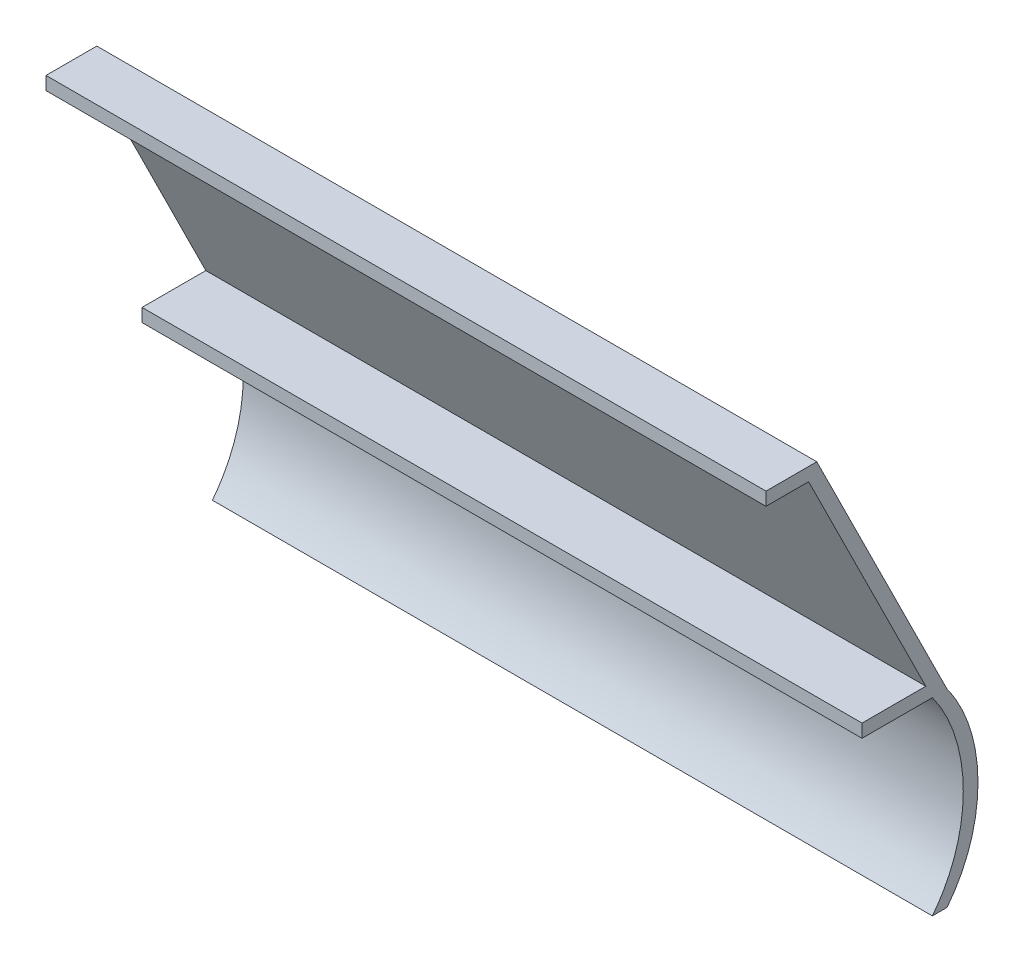
SolidWorks part; units mm, degrees
ref_plane "前视基准面" through (0, 0, 0) normal (0, 0, 1) x (1, 0, 0)
ref_plane "上视基准面" through (0, 0, 0) normal (0, 1, 0) x (1, 0, 0)
ref_plane "右视基准面" through (0, 0, 0) normal (1, 0, 0) x (0, 0, -1)
sketch "草图1" plane through (0, 0, 0) normal (1, 0, 0) x (0, 0, -1)
  line L0 (0, 0) -> (9.7, 0) construction
  line L1 (9.7, 0) -> (9.7, -56.63) construction
  line L2 (9.7, -56.63) -> (37.85, -56.63) construction
  line L3 (9.7, 0) -> (36.3587, -53.63)
  line L4 (37.85, -56.63) -> (37.85, -99.63) construction
  line L5 (0, 0) -> (0, 3)
  line L6 (12.8929, 0.3164) -> (41.0429, -56.3136)
  line L7 (0, 3) -> (11.5589, 3)
  line L8 (12.8929, 0.3164) -> (11.5589, 3)
  line L9 (41.0429, -56.3136) -> (41.2002, -56.63)
  line L10 (41.2002, -99.63) -> (37.85, -99.63)
  line L11 (0, 0) -> (9.7, 0)
  line L12 (37.85, -56.63) -> (21.85, -56.63)
  line L13 (21.85, -56.63) -> (21.85, -53.63)
  line L14 (21.85, -53.63) -> (36.3587, -53.63)
  spline S0 degree 3 poles (37.85, -56.63) (46.954, -69.0607) (47.4998, -87.4222) (37.85, -99.63) knots 0 0 0 0 1 1 1 1
  spline S1 degree 3 poles (41.2002, -56.63) (50.3042, -69.0607) (50.85, -87.4222) (41.2002, -99.63) knots 0 0 0 0 1 1 1 1
  dimension "D1" = 9.7
  dimension "D2" = 56.63
  dimension "D3" = 28.15
  dimension "D4" = 43
  dimension "D5" = 3
  dimension "D6" = 3
  dimension "D7" = 16
  dimension "D8" = 3
extrude "凸台-拉伸1" add sketch "草图1" along normal blind 163.8
